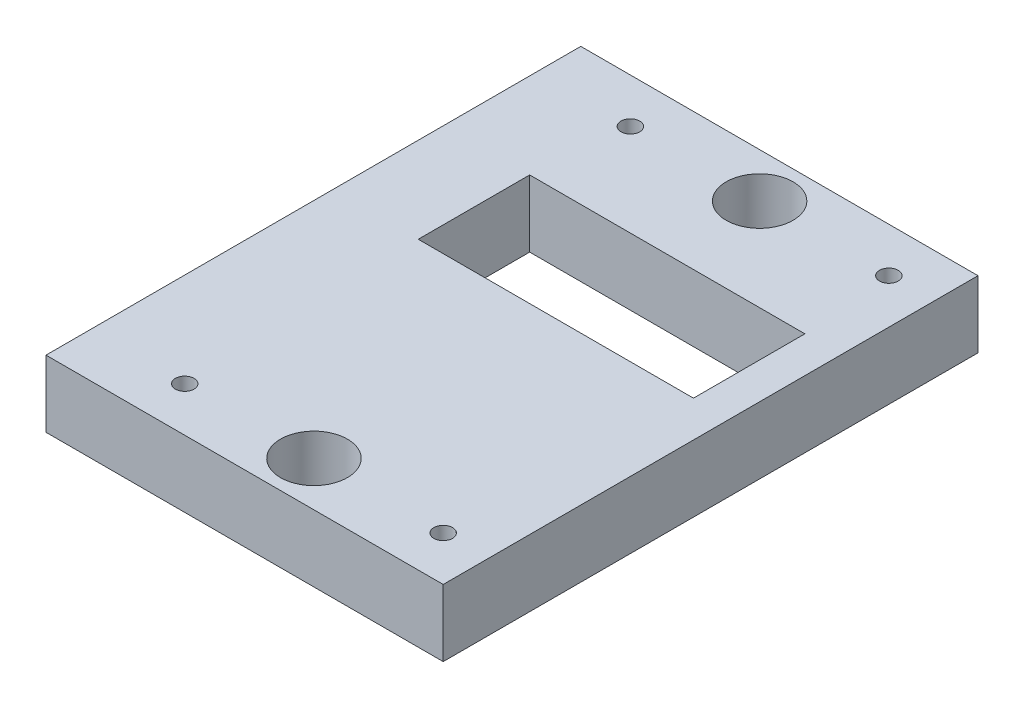
SolidWorks part; units mm, degrees
material "Plain Carbon Steel"
ref_plane "Front Plane" through (0, 0, 0) normal (0, 0, 1) x (1, 0, 0)
ref_plane "Top Plane" through (0, 0, 0) normal (0, 1, 0) x (1, 0, 0)
ref_plane "Right Plane" through (0, 0, 0) normal (1, 0, 0) x (0, 0, -1)
sketch "Sketch1" plane through (0, 0, 0) normal (0, 1, 0) x (1, 0, 0)
  line L0 (-89.125, 0) -> (-89.125, -120) construction
  line L5 (-89.125, -120) -> (0, -120)
  line L6 (-89.125, -120) -> (-89.125, 0)
  line L7 (-89.125, 0) -> (0, 0)
  line L8 (0, -120) -> (0, 0)
  dimension "D1" = 120
extrude "Boss-Extrude1" add sketch "Sketch1" along normal mid plane 15
sketch "Sketch3" plane through (0, 7.5, 0) normal (0, 1, 0) x (1, 0, 0)
  line L1 (-69.875, -30.72) -> (-8.125, -30.72)
  line L2 (-69.875, -30.72) -> (-69.875, -55.72)
  line L3 (-69.875, -55.72) -> (-8.125, -55.72)
  line L4 (-8.125, -30.72) -> (-8.125, -55.72)
extrude "Cut-Extrude1" cut sketch "Sketch3" against normal up to next
sketch "Sketch4" plane through (0, 7.5, 0) normal (0, 1, 0) x (1, 0, 0)
  circle A0 centre (-39, -10) radius 7.5 construction
  circle A1 centre (-39, -110) radius 7.5 construction
  circle A2 centre (-39, -10) radius 7.5
  circle A3 centre (-39, -110) radius 7.5
extrude "Cut-Extrude2" cut sketch "Sketch4" against normal up to next
hole_wizard "M5 Tapped Hole1" positions "Sketch11" profile "Sketch8" tap size "M5" standard "ISO" end condition through all
sketch "Sketch11" plane through (0, -7.5, 0) normal (0, -1, 0) x (-1, 0, 0)
  line L0 (0, 0) -> (89.125, 0) construction
  line L1 (0, -120) -> (0, 0) construction
  line L3 (89.125, -120) -> (0, -120) construction
  circle A0 centre (39, -10) radius 7.5 construction
  point P0 (10, -10)
  point P2 (68, -10)
  point P4 (68, -110)
  point P6 (10, -110)
  dimension "D1" = 10
  dimension "D2" = 10
  dimension "D3" = 29
  dimension "D4" = 10
  dimension "D5" = 29
sketch "Sketch8" plane through (-10, -7.5, 10) normal (1, 0, 0) x (0, 0, -1)
  line L0 (0, 0) -> (0, 15)
  line L1 (0, 15) -> (2.1, 15)
  line L2 (2.1, 15) -> (2.1, 0)
  line L5 (2.1, 0) -> (0, 0)
  line L11 (0, -6.35) -> (0, 107.95) construction
  dimension "Thru Tap Drill Dia." = 4.2
  dimension "Thru Tap Drill Depth" = 15
cosmetic thread "Hole Thread1" parameters "D2"=5
cosmetic thread "Hole Thread2" parameters "D2"=5
cosmetic thread "Hole Thread3" parameters "D2"=5
cosmetic thread "Hole Thread4" parameters "D2"=5
sketch "Sketch10" plane through (0, -7.5, 0) normal (0, -1, 0) x (1, 0, 0)
  circle A0 centre (-68, 110) radius 6.25
  circle A1 centre (-10, 110) radius 6.25
  circle A2 centre (-68, 10) radius 6.25
  circle A3 centre (-10, 10) radius 6.25
  dimension "D1" = 12.5
extrude "Cut-Extrude3" cut sketch "Sketch10" against normal blind 5
